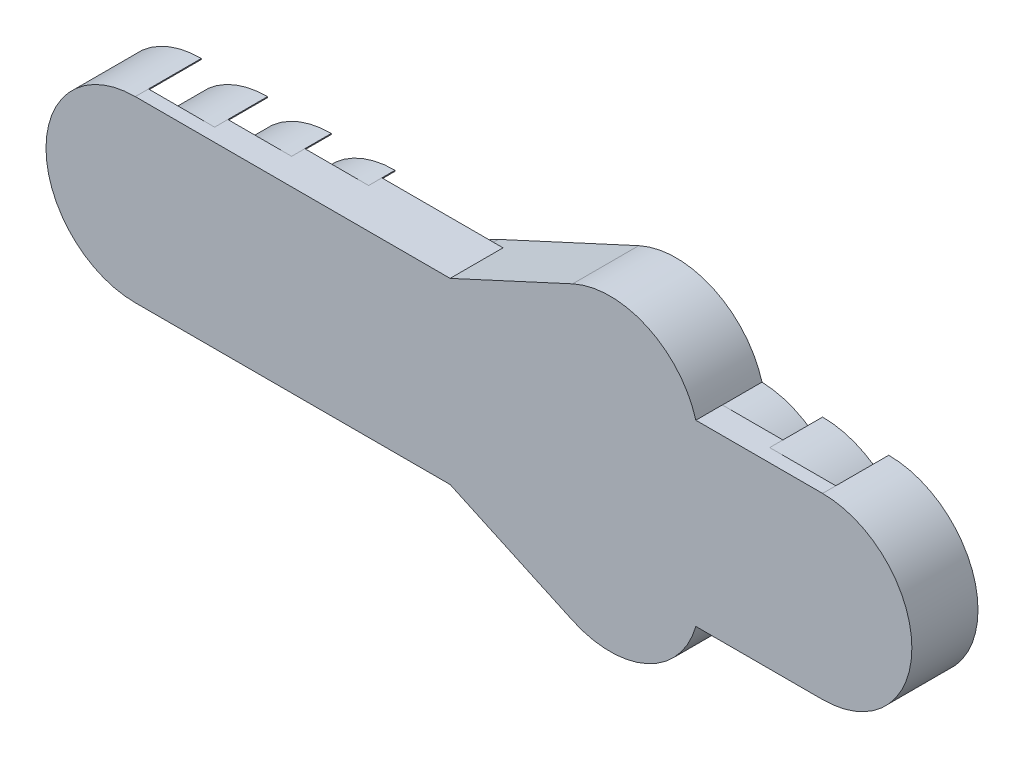
SolidWorks part; units mm, degrees
ref_plane "Front Plane" through (0, 0, 0) normal (0, 0, 1) x (1, 0, 0)
ref_plane "Top Plane" through (0, 0, 0) normal (0, 1, 0) x (1, 0, 0)
ref_plane "Right Plane" through (0, 0, 0) normal (1, 0, 0) x (0, 0, -1)
sketch "Sketch1" plane through (0, 0, 0) normal (0, 0, 1) x (1, 0, 0)
  line L1 (-31.75, 18.9) -> (31.75, 18.9)
  line L2 (-31.75, 18.9) -> (-31.75, -18.9) construction
  line L3 (-31.75, -18.9) -> (31.75, -18.9)
  line L4 (31.75, 18.9) -> (31.75, -18.9) construction
  line L5 (-31.75, 18.9) -> (31.75, -18.9) construction
  line L6 (-31.75, -18.9) -> (31.75, 18.9) construction
  arc A0 (-31.75, 18.9) -> (-31.75, -18.9) centre (-31.75, 0) ccw
  arc A1 (31.75, 18.9) -> (31.75, -18.9) centre (31.75, 0) cw
  point P0 (0, 0)
  point P8 (-50.65, 0)
  point P9 (50.65, 0)
  dimension "D1" = 37.8
  dimension "D2" = 101.3
extrude "Boss-Extrude1" add sketch "Sketch1" along normal blind 2.8
sketch "Sketch5" plane through (0, 0, 0) normal (0, 0, -1) x (-1, 0, 0)
  line L4 (-25.9419, 32.6) -> (-126.1347, 32.6) construction
  line L5 (47.072, 0) -> (-46.65, 0) construction
  line L6 (-46.65, 0) -> (-46.65, 43.232) construction
  line L7 (-46.65, 43.232) -> (47.072, 0) construction
  line L8 (20.85, -23.5132) -> (20.85, 2.4291) construction
  line L9 (-46.65, -13.7) -> (-46.65, 13.7)
  line L10 (-19.8335, 30.8621) -> (9.8665, 17.1621)
  line L11 (-19.8335, -30.8621) -> (9.8665, -17.1621)
  arc A3 (9.8665, -17.1621) -> (9.8665, 17.1621) centre (1.95, 0) ccw
  arc A4 (-46.65, 13.7) -> (-19.8335, 30.8621) centre (-27.75, 13.7) cw
  arc A5 (-46.65, -13.7) -> (-19.8335, -30.8621) centre (-27.75, -13.7) ccw
  arc A7 (-31.75, 18.9) -> (-31.75, -18.9) centre (-31.75, 0) ccw construction
  point P11 (20.85, 0)
  point P13 (0, 0)
  point P30 (-50.65, 0)
  dimension "D1" = 18.9
  dimension "D3" = 67.5
  dimension "D2" = 32.6
  dimension "D4" = 4
extrude "Boss-Extrude5" add sketch "Sketch5" along normal blind 2.8
sketch "Sketch2" plane through (0, 0, 2.8) normal (0, 0, 1) x (1, 0, 0)
  line L0 (31.75, 18.9) -> (-31.75, 18.9) construction
  line L1 (-45.25, 18.9) -> (45.25, 18.9)
  line L2 (-45.25, 18.9) -> (-45.25, -18.9) construction
  line L3 (-45.25, -18.9) -> (45.25, -18.9)
  line L4 (45.25, 18.9) -> (45.25, -18.9) construction
  line L5 (-45.25, 18.9) -> (45.25, -18.9) construction
  line L6 (-45.25, -18.9) -> (45.25, 18.9) construction
  arc A0 (-45.25, 18.9) -> (-45.25, -18.9) centre (-45.25, 0) ccw
  arc A1 (45.25, 18.9) -> (45.25, -18.9) centre (45.25, 0) cw
  point P0 (0, 0)
  point P11 (-64.15, 0)
  point P12 (64.15, 0)
  dimension "D1" = 128.3
extrude "Boss-Extrude2" add sketch "Sketch2" along normal blind 2.8
sketch "Sketch3" plane through (0, 0, 5.6) normal (0, 0, 1) x (1, 0, 0)
  line L0 (45.25, 18.9) -> (-45.25, 18.9) construction
  line L1 (-58.75, 18.9) -> (58.75, 18.9)
  line L2 (-58.75, 18.9) -> (-58.75, -18.9) construction
  line L3 (-58.75, -18.9) -> (58.75, -18.9)
  line L4 (58.75, 18.9) -> (58.75, -18.9) construction
  line L5 (-58.75, 18.9) -> (58.75, -18.9) construction
  line L6 (-58.75, -18.9) -> (58.75, 18.9) construction
  arc A0 (-58.75, 18.9) -> (-58.75, -18.9) centre (-58.75, 0) ccw
  arc A1 (58.75, 18.9) -> (58.75, -18.9) centre (58.75, 0) cw
  point P0 (0, 0)
  point P10 (-77.65, 0)
  point P11 (77.65, 0)
  dimension "D1" = 155.3
extrude "Boss-Extrude3" add sketch "Sketch3" along normal blind 2.8
sketch "Sketch4" plane through (0, 0, 8.4) normal (0, 0, 1) x (1, 0, 0)
  line L0 (58.75, 18.9) -> (-58.75, 18.9) construction
  line L1 (-72.75, 18.9) -> (72.75, 18.9)
  line L2 (-72.75, 18.9) -> (-72.75, -18.9) construction
  line L3 (-72.75, -18.9) -> (72.75, -18.9)
  line L4 (72.75, 18.9) -> (72.75, -18.9) construction
  line L5 (-72.75, 18.9) -> (72.75, -18.9) construction
  line L6 (-72.75, -18.9) -> (72.75, 18.9) construction
  arc A0 (-72.75, 18.9) -> (-72.75, -18.9) centre (-72.75, 0) ccw
  arc A1 (72.75, 18.9) -> (72.75, -18.9) centre (72.75, 0) cw
  point P0 (0, 0)
  point P10 (-91.65, 0)
  point P11 (91.65, 0)
  dimension "D1" = 183.3
extrude "Boss-Extrude4" add sketch "Sketch4" along normal blind 2.8
sketch "Sketch7" plane through (0, 0, 0) normal (0, 0, 1) x (1, 0, 0)
  line L3 (31.75, -18.9) -> (-6.099, -18.9)
  line L4 (-6.099, -18.9) -> (19.8335, -30.8621)
  line L5 (46.65, -13.7) -> (46.65, -11.6276)
  line L6 (31.75, -18.9) -> (-6.099, -18.9)
  line L7 (-6.099, -18.9) -> (19.8335, -30.8621)
  line L8 (46.65, -13.7) -> (46.65, -11.6276)
  line L9 (46.65, 11.6276) -> (46.65, 13.7)
  line L10 (19.8335, 30.8621) -> (-6.099, 18.9)
  line L11 (-6.099, 18.9) -> (31.75, 18.9)
  line L12 (46.65, 11.6276) -> (46.65, 13.7)
  line L13 (19.8335, 30.8621) -> (-6.099, 18.9)
  line L14 (-6.099, 18.9) -> (31.75, 18.9)
  arc A2 (31.75, -18.9) -> (46.65, -11.6276) centre (31.75, 0) ccw
  arc A3 (19.8335, -30.8621) -> (46.65, -13.7) centre (27.75, -13.7) ccw
  arc A4 (31.75, -18.9) -> (46.65, -11.6276) centre (31.75, 0) ccw
  arc A5 (19.8335, -30.8621) -> (46.65, -13.7) centre (27.75, -13.7) ccw
  arc A6 (46.65, 11.6276) -> (31.75, 18.9) centre (31.75, 0) ccw
  arc A7 (46.65, 13.7) -> (19.8335, 30.8621) centre (27.75, 13.7) ccw
  arc A8 (46.65, 11.6276) -> (31.75, 18.9) centre (31.75, 0) ccw
  arc A9 (46.65, 13.7) -> (19.8335, 30.8621) centre (27.75, 13.7) ccw
  dimension "D1" = 0
  dimension "D2" = 0
extrude "Boss-Extrude6" add sketch "Sketch7" along normal up to surface (11.2 mm away) up to face at (0, 0, 11.2)
sketch "Sketch10" plane through (0, 0, -2.8) normal (0, 0, -1) x (-1, 0, 0)
  arc A0 (18.0098, -9.9646) -> (18.0098, 9.9646) centre (18.85, 0) ccw
  arc A1 (9.8665, -17.1621) -> (9.8665, 17.1621) centre (1.95, 0) ccw construction
  arc A2 (18.0098, -9.9646) -> (18.0098, 9.9646) centre (1.95, 0) ccw
  point P3 (28.85, 0)
  point P10 (20.85, 0)
  dimension "D1" = 8
  dimension "D2" = 10
extrude "Boss-Extrude7" add sketch "Sketch10" against normal up to surface (2.8 mm away) up to face at (-20.8858, 0, 0)
sketch "Sketch11" plane through (0, 0, 8.4) normal (0, 0, -1) x (-1, 0, 0)
  line L0 (-72.75, -18.7) -> (-72.75, -18.9)
  line L1 (-72.75, 18.9) -> (-72.75, 18.7)
  line L3 (72.75, -18.7) -> (72.75, -18.9)
  line L4 (72.75, 18.9) -> (72.75, 18.7)
  arc A0 (-72.75, 18.9) -> (-72.75, -18.9) centre (-72.75, 0) ccw construction
  arc A1 (-72.75, 18.9) -> (-72.75, -18.9) centre (-72.75, 0) ccw
  arc A2 (72.75, -18.9) -> (72.75, 18.9) centre (72.75, 0) ccw construction
  arc A3 (72.75, -18.9) -> (72.75, 18.9) centre (72.75, 0) ccw
  arc A4 (-72.75, 18.7) -> (-72.75, -18.7) centre (-72.75, 0) ccw
  arc A5 (72.75, -18.7) -> (72.75, 18.7) centre (72.75, 0) ccw
  point P12 (-72.7298, 18.7)
  point P13 (72.75, -18.8832)
  point P14 (-72.75, -18.9054)
  point P17 (0, 0)
  dimension "D1" = 0.2
extrude "Boss-Extrude8" add sketch "Sketch11" along normal up to surface (11.2 mm away) up to face at (9.3387, 0, -2.8)
sketch "Sketch12" plane through (0, 0, 5.6) normal (0, 0, -1) x (-1, 0, 0)
  line L0 (-58.75, 18.9) -> (-58.75, 18.7)
  line L1 (-58.75, -18.7) -> (-58.75, -18.9)
  line L2 (58.75, 18.9) -> (58.75, 18.7)
  line L3 (58.75, -18.7) -> (58.75, -18.9)
  arc A0 (58.75, -18.9) -> (58.75, 18.9) centre (58.75, 0) ccw construction
  arc A1 (-58.75, 18.9) -> (-58.75, -18.9) centre (-58.75, 0) ccw construction
  arc A2 (58.75, -18.9) -> (58.75, 18.9) centre (58.75, 0) ccw
  arc A3 (-58.75, 18.9) -> (-58.75, -18.9) centre (-58.75, 0) ccw
  arc A4 (-58.75, 18.7) -> (-58.75, -18.7) centre (-58.75, 0) ccw
  arc A5 (58.75, -18.7) -> (58.75, 18.7) centre (58.75, 0) ccw
  dimension "D1" = 0.2
extrude "Boss-Extrude9" add sketch "Sketch12" along normal up to surface (8.4 mm away) up to face at (9.3387, 0, -2.8)
sketch "Sketch13" plane through (0, 0, 2.8) normal (0, 0, -1) x (-1, 0, 0)
  line L0 (-45.924, 18.888) -> (-45.9169, 18.6881)
  line L1 (-45.924, -18.888) -> (-45.9169, -18.6881)
  line L2 (45.25, 18.9) -> (45.25, 18.7)
  line L3 (45.25, -18.7) -> (45.25, -18.9)
  arc A0 (45.25, -18.9) -> (45.25, 18.9) centre (45.25, 0) ccw construction
  arc A1 (-45.924, 18.888) -> (-45.924, -18.888) centre (-45.25, 0) ccw construction
  arc A2 (45.25, -18.9) -> (45.25, 18.9) centre (45.25, 0) ccw
  arc A3 (-45.924, 18.888) -> (-45.924, -18.888) centre (-45.25, 0) ccw
  arc A4 (-45.9169, 18.6881) -> (-45.9169, -18.6881) centre (-45.25, 0) ccw
  arc A5 (45.25, -18.7) -> (45.25, 18.7) centre (45.25, 0) ccw
  dimension "D1" = 0.2
extrude "Boss-Extrude10" add sketch "Sketch13" along normal up to surface (5.6 mm away) up to face at (9.3387, 0, -2.8)
sketch "Sketch14" plane through (0, 0, 0) normal (0, 0, -1) x (-1, 0, 0)
  line L0 (-46.65, -11.6276) -> (-46.4923, -11.5045)
  line L1 (-46.65, 11.6276) -> (-46.4923, 11.5045)
  line L2 (31.75, 18.9) -> (31.75, 18.7)
  line L3 (31.75, -18.7) -> (31.75, -18.9)
  arc A0 (31.75, -18.9) -> (31.75, 18.9) centre (31.75, 0) ccw construction
  arc A1 (-46.65, 11.6276) -> (-46.65, -11.6276) centre (-31.75, 0) ccw construction
  arc A2 (31.75, -18.9) -> (31.75, 18.9) centre (31.75, 0) ccw
  arc A3 (-46.65, 11.6276) -> (-46.65, -11.6276) centre (-31.75, 0) ccw
  arc A4 (-46.4923, 11.5045) -> (-46.4923, -11.5045) centre (-31.75, 0) ccw
  arc A5 (31.75, -18.7) -> (31.75, 18.7) centre (31.75, 0) ccw
  dimension "D1" = 0.2
extrude "Boss-Extrude11" add sketch "Sketch14" along normal up to surface (2.8 mm away) up to face at (50.8909, 0, -2.8)
